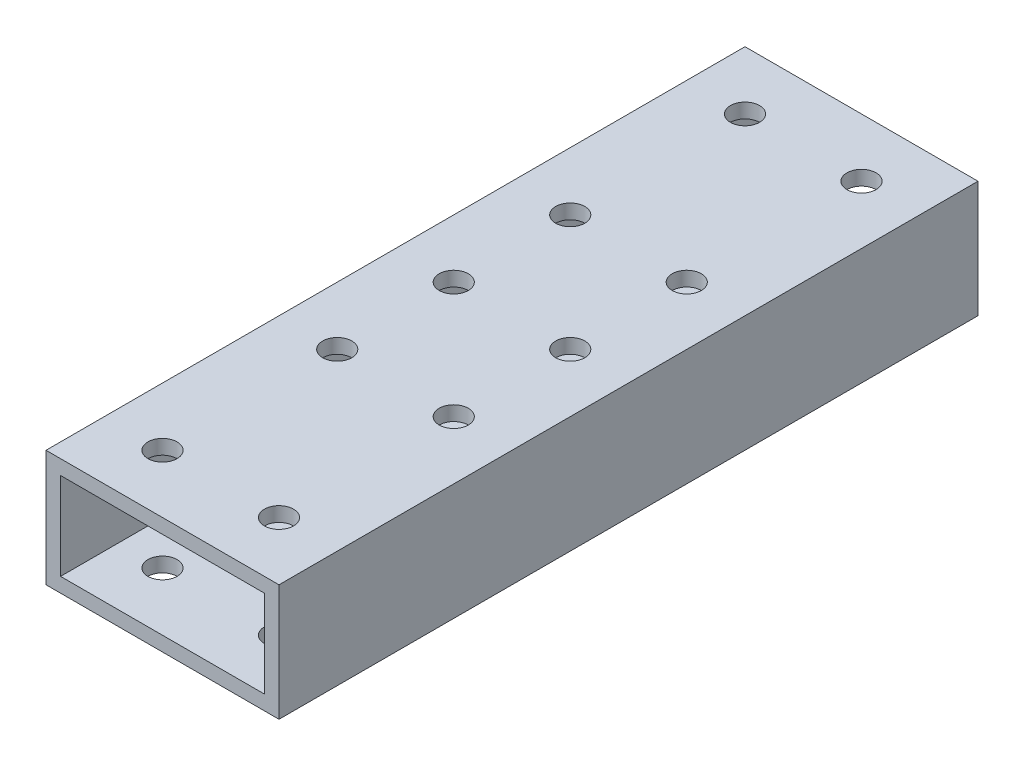
SolidWorks part; units mm, degrees
ref_plane "Front Plane" through (0, 0, 0) normal (0, 0, 1) x (1, 0, 0)
ref_plane "Top Plane" through (0, 0, 0) normal (0, 1, 0) x (1, 0, 0)
ref_plane "Right Plane" through (0, 0, 0) normal (1, 0, 0) x (0, 0, -1)
sketch "Sketch1" plane through (0, 0, 0) normal (0, 0, 1) x (1, 0, 0)
  line L0 (3.175, 22.225) -> (47.625, 22.225)
  line L1 (0, 0) -> (50.8, 0)
  line L2 (0, 0) -> (0, 25.4)
  line L3 (0, 25.4) -> (50.8, 25.4)
  line L4 (50.8, 0) -> (50.8, 25.4)
  line L5 (47.625, 3.175) -> (47.625, 22.225)
  line L6 (3.175, 3.175) -> (47.625, 3.175)
  line L7 (3.175, 3.175) -> (3.175, 22.225)
  dimension "D2" = 50.8
  dimension "D3" = 25.4
  dimension "D1" = 3.175
extrude "Boss-Extrude1" add sketch "Sketch1" along normal blind 152.4
sketch "Sketch2" plane through (0, 25.4, 0) normal (0, 1, 0) x (1, 0, 0)
  line L0 (25.4, 0) -> (25.4, -152.4) construction
  line L1 (50.8, 0) -> (0, 0) construction
  line L2 (50.8, -152.4) -> (0, -152.4) construction
  line L3 (25.4, -76.2) -> (12.7, -76.2) construction
  line L4 (12.7, -76.2) -> (12.7, -50.8) construction
  line L5 (12.7, -50.8) -> (12.7, -12.7) construction
  circle A0 centre (12.7, -12.7) radius 3.175
  circle A1 centre (12.7, -50.8) radius 3.175
  circle A2 centre (12.7, -76.2) radius 3.175
  circle A3 centre (12.7, -101.6) radius 3.175
  circle A4 centre (12.7, -139.7) radius 3.175
  circle A5 centre (38.1, -139.7) radius 3.175
  circle A6 centre (38.1, -101.6) radius 3.175
  circle A7 centre (38.1, -76.2) radius 3.175
  circle A8 centre (38.1, -12.7) radius 3.175
  circle A9 centre (38.1, -50.8) radius 3.175
  dimension "D4" = 6.35
  dimension "D1" = 25.4
  dimension "D2" = 12.7
  dimension "D3" = 38.1
extrude "Cut-Extrude1" cut sketch "Sketch2" against normal through all both and the other way through all
